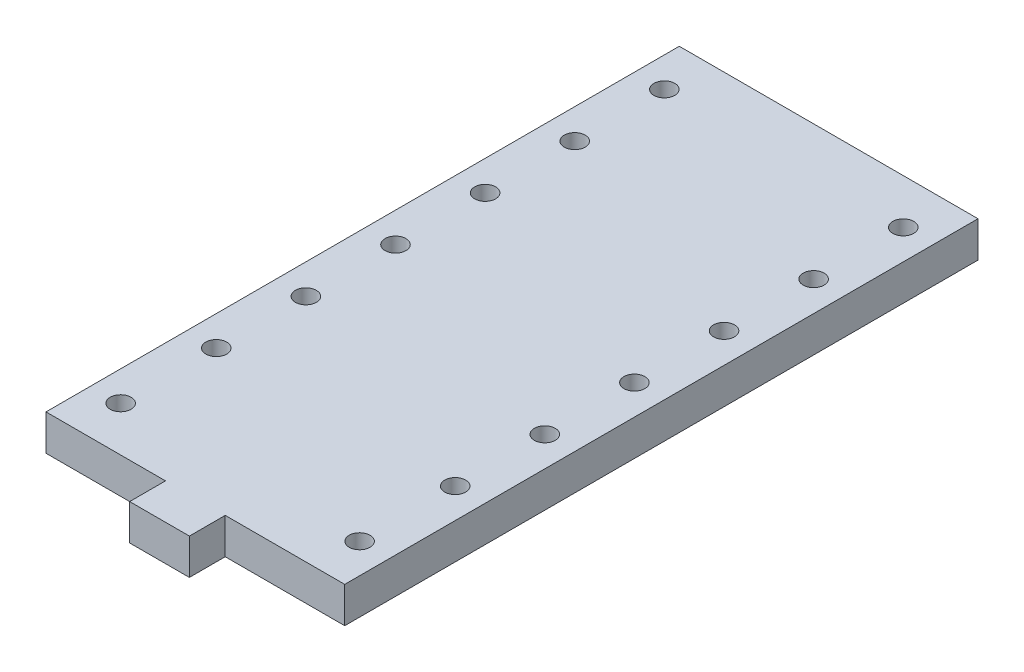
SolidWorks part; units mm, degrees
ref_plane "Plano frontal" through (0, 0, 0) normal (0, 0, 1) x (1, 0, 0)
ref_plane "Plano superior" through (0, 0, 0) normal (0, 1, 0) x (1, 0, 0)
ref_plane "Plano direito" through (0, 0, 0) normal (1, 0, 0) x (0, 0, -1)
sketch "Esboço1" plane through (0, 0, 0) normal (0, 1, 0) x (1, 0, 0)
  line L1 (2.8639, 0) -> (-47.1361, 0)
  line L2 (2.8639, 0) -> (2.8639, 112)
  line L3 (2.8639, 112) -> (-47.1361, 112)
  line L4 (-47.1361, 0) -> (-47.1361, 112)
  dimension "D1" = 112
  dimension "D2" = 50
extrude "Ressalto-extrusão1" add sketch "Esboço1" along normal blind 6
sketch "Esboço2" plane through (0, 0, 0) normal (0, 0, 1) x (1, 0, 0)
  line L0 (-47.1361, 0) -> (2.8639, 0) construction
  line L1 (-47.1361, 6) -> (-27.1361, 6)
  line L2 (-47.1361, 6) -> (-47.1361, 0)
  line L3 (-47.1361, 0) -> (-27.1361, 0)
  line L4 (-27.1361, 6) -> (-27.1361, 0)
  line L6 (2.8639, 6) -> (-17.1361, 6)
  line L7 (2.8639, 6) -> (2.8639, 0)
  line L8 (2.8639, 0) -> (-17.1361, 0)
  line L9 (-17.1361, 6) -> (-17.1361, 0)
  dimension "D1" = 20
  dimension "D2" = 20
extrude "Corte-extrusão1" cut sketch "Esboço2" against normal blind 6
sketch "Esboço5" plane through (0, 6, 0) normal (0, 1, 0) x (1, 0, 0)
  line L0 (-42.1361, 112) -> (-42.1361, 6) construction
  line L1 (2.8639, 112) -> (-47.1361, 112) construction
  line L2 (-27.1361, 6) -> (-47.1361, 6) construction
  line L3 (-2.1361, 111.9917) -> (-2.1361, 6) construction
  line L4 (2.8639, 6) -> (2.8639, 112) construction
  line L7 (-47.1361, 112) -> (-47.1361, 6) construction
  circle A0 centre (-42.1361, 104.5) radius 1.75
  circle A1 centre (-42.1361, 89.5) radius 1.75
  circle A2 centre (-42.1361, 74.5) radius 1.75
  circle A3 centre (-42.1361, 59.5) radius 1.75
  circle A4 centre (-42.1361, 44.5) radius 1.75
  circle A5 centre (-42.1361, 13.5) radius 1.75
  circle A6 centre (-42.1361, 29.5) radius 1.75
  circle A7 centre (-2.1361, 104.4917) radius 1.75
  circle A8 centre (-2.1361, 89.4917) radius 1.75
  circle A9 centre (-2.1361, 74.4917) radius 1.75
  circle A10 centre (-2.1361, 59.4917) radius 1.75
  circle A11 centre (-2.1361, 44.4917) radius 1.75
  circle A12 centre (-2.1361, 13.4917) radius 1.75
  circle A13 centre (-2.1361, 29.4917) radius 1.75
  point P40 (-2.1361, 6)
  point P41 (0, 0)
  dimension "D3" = 3.5
  dimension "D4" = 3.5
  dimension "D5" = 3.5
  dimension "D6" = 3.5
  dimension "D7" = 3.5
  dimension "D8" = 3.5
  dimension "D10" = 7.5
  dimension "D15" = 3.5
  dimension "D2" = 5
  dimension "D9" = 7.5
  dimension "D11" = 15
  dimension "D12" = 15
  dimension "D13" = 15
  dimension "D14" = 15
  dimension "D16" = 15
  dimension "D17" = 5
extrude "Corte-extrusão3" cut sketch "Esboço5" against normal blind 6
